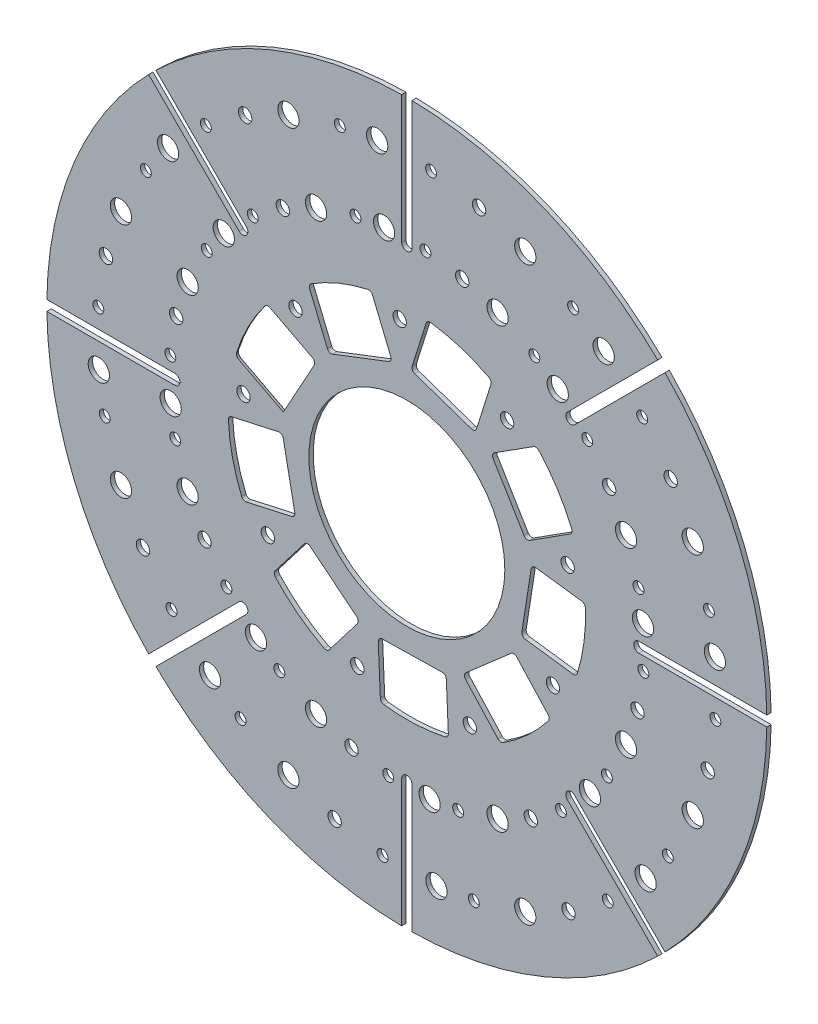
SolidWorks part; units mm, degrees
ref_plane "Plano frontal" through (0, 0, 0) normal (0, 0, 1) x (1, 0, 0)
ref_plane "Plano superior" through (0, 0, 0) normal (0, 1, 0) x (1, 0, 0)
ref_plane "Plano direito" through (0, 0, 0) normal (1, 0, 0) x (0, 0, -1)
sketch "Esboço1" plane through (0, 0, 0) normal (0, 0, 1) x (1, 0, 0)
  circle A0 centre (0, 0) radius 174.5
  circle A1 centre (0, 0) radius 47.5
  dimension "D1" = 349
  dimension "D2" = 95
extrude "Ressalto-extrusão1" add sketch "Esboço1" along normal blind 2.1
sketch "Esboço2" plane through (0, 0, 2.1) normal (0, 0, 1) x (1, 0, 0)
  line L0 (0, 174.5) -> (0, 64.5) construction
  line L1 (-2.5, 239.1223) -> (2.5, 239.1223)
  line L2 (0, 64.5) -> (0, 95.0835) construction
  line L3 (-2.5, 239.1223) -> (-2.5, 112.5)
  line L4 (2.5, 239.1223) -> (2.5, 112.5)
  line L5 (167.3172, 170.8527) -> (170.8527, 167.3172)
  line L6 (167.3172, 170.8527) -> (77.7817, 81.3173)
  line L7 (170.8527, 167.3172) -> (81.3173, 77.7817)
  line L8 (239.1223, 2.5) -> (239.1223, -2.5)
  line L9 (239.1223, 2.5) -> (112.5, 2.5)
  line L10 (239.1223, -2.5) -> (112.5, -2.5)
  line L11 (170.8527, -167.3172) -> (167.3172, -170.8527)
  line L12 (170.8527, -167.3172) -> (81.3173, -77.7817)
  line L13 (167.3172, -170.8527) -> (77.7817, -81.3173)
  line L14 (2.5, -239.1223) -> (-2.5, -239.1223)
  line L15 (2.5, -239.1223) -> (2.5, -112.5)
  line L16 (-2.5, -239.1223) -> (-2.5, -112.5)
  line L17 (-167.3172, -170.8527) -> (-170.8527, -167.3172)
  line L18 (-167.3172, -170.8527) -> (-77.7817, -81.3173)
  line L19 (-170.8527, -167.3172) -> (-81.3173, -77.7817)
  line L20 (-239.1223, -2.5) -> (-239.1223, 2.5)
  line L21 (-239.1223, -2.5) -> (-112.5, -2.5)
  line L22 (-239.1223, 2.5) -> (-112.5, 2.5)
  line L23 (-170.8527, 167.3172) -> (-167.3172, 170.8527)
  line L24 (-170.8527, 167.3172) -> (-81.3173, 77.7817)
  line L25 (-167.3172, 170.8527) -> (-77.7817, 81.3173)
  circle A0 centre (0, 0) radius 174.5 construction
  arc A1 (-2.5, 112.5) -> (2.5, 112.5) centre (0, 112.5) ccw
  arc A2 (77.7817, 81.3173) -> (81.3173, 77.7817) centre (79.5495, 79.5495) ccw
  arc A3 (112.5, 2.5) -> (112.5, -2.5) centre (112.5, 0) ccw
  arc A4 (81.3173, -77.7817) -> (77.7817, -81.3173) centre (79.5495, -79.5495) ccw
  arc A5 (2.5, -112.5) -> (-2.5, -112.5) centre (0, -112.5) ccw
  arc A6 (-77.7817, -81.3173) -> (-81.3173, -77.7817) centre (-79.5495, -79.5495) ccw
  arc A7 (-112.5, -2.5) -> (-112.5, 2.5) centre (-112.5, 0) ccw
  arc A8 (-81.3173, 77.7817) -> (-77.7817, 81.3173) centre (-79.5495, 79.5495) ccw
  point P49 (0, 0)
  dimension "D1" = 2.5
  dimension "D3" = 62
sketch "Esboço3" plane through (0, 0, 2.1) normal (0, 0, 1) x (1, 0, 0)
  line L0 (0, 0) -> (-225.1004, 0) construction
  line L1 (0, 0) -> (-138.5819, 57.4025) construction
  line L2 (0, 0) -> (-126.5087, 80.5949) construction
  line L3 (0, 0) -> (-115.7437, 95.4117) construction
  line L4 (0, 0) -> (-145.8555, 35.0168) construction
  line L5 (0, 0) -> (-149.5376, 11.7689) construction
  circle A0 centre (0, 0) radius 115 construction
  circle A1 centre (0, 0) radius 150 construction
  circle A2 centre (-138.5819, 57.4025) radius 5.15
  circle A3 centre (-106.2461, 44.0086) radius 5.15
  circle A4 centre (-126.5087, 80.5949) radius 2.65
  circle A5 centre (-96.99, 61.7895) radius 2.65
  circle A6 centre (-115.7437, 95.4117) radius 5.15
  circle A7 centre (-88.7368, 73.149) radius 5.15
  circle A8 centre (-145.8555, 35.0168) radius 3.25
  circle A9 centre (-111.8225, 26.8462) radius 3.25
  circle A10 centre (-114.6455, 9.0228) radius 2.65
  circle A11 centre (-149.5376, 11.7689) radius 2.65
  circle A12 centre (-57.4025, 138.5819) radius 5.15
  circle A13 centre (-44.0086, 106.2461) radius 5.15
  circle A14 centre (-32.4659, 146.4444) radius 2.65
  circle A15 centre (-24.8906, 112.274) radius 2.65
  circle A16 centre (-14.3769, 149.3094) radius 5.15
  circle A17 centre (-11.0223, 114.4706) radius 5.15
  circle A18 centre (-78.3748, 127.896) radius 3.25
  circle A19 centre (-60.0873, 98.0536) radius 3.25
  circle A20 centre (-74.6865, 87.4467) radius 2.65
  circle A21 centre (-97.4172, 114.0609) radius 2.65
  circle A22 centre (57.4025, 138.5819) radius 5.15
  circle A23 centre (44.0086, 106.2461) radius 5.15
  circle A24 centre (80.5949, 126.5087) radius 2.65
  circle A25 centre (61.7895, 96.99) radius 2.65
  circle A26 centre (95.4117, 115.7437) radius 5.15
  circle A27 centre (73.149, 88.7368) radius 5.15
  circle A28 centre (35.0168, 145.8555) radius 3.25
  circle A29 centre (26.8462, 111.8225) radius 3.25
  circle A30 centre (9.0228, 114.6455) radius 2.65
  circle A31 centre (11.7689, 149.5376) radius 2.65
  circle A32 centre (138.5819, 57.4025) radius 5.15
  circle A33 centre (106.2461, 44.0086) radius 5.15
  circle A34 centre (146.4444, 32.4659) radius 2.65
  circle A35 centre (112.274, 24.8906) radius 2.65
  circle A36 centre (149.3094, 14.3769) radius 5.15
  circle A37 centre (114.4706, 11.0223) radius 5.15
  circle A38 centre (127.896, 78.3748) radius 3.25
  circle A39 centre (98.0536, 60.0873) radius 3.25
  circle A40 centre (87.4467, 74.6865) radius 2.65
  circle A41 centre (114.0609, 97.4172) radius 2.65
  circle A42 centre (138.5819, -57.4025) radius 5.15
  circle A43 centre (106.2461, -44.0086) radius 5.15
  circle A44 centre (126.5087, -80.5949) radius 2.65
  circle A45 centre (96.99, -61.7895) radius 2.65
  circle A46 centre (115.7437, -95.4117) radius 5.15
  circle A47 centre (88.7368, -73.149) radius 5.15
  circle A48 centre (145.8555, -35.0168) radius 3.25
  circle A49 centre (111.8225, -26.8462) radius 3.25
  circle A50 centre (114.6455, -9.0228) radius 2.65
  circle A51 centre (149.5376, -11.7689) radius 2.65
  circle A52 centre (57.4025, -138.5819) radius 5.15
  circle A53 centre (44.0086, -106.2461) radius 5.15
  circle A54 centre (32.4659, -146.4444) radius 2.65
  circle A55 centre (24.8906, -112.274) radius 2.65
  circle A56 centre (14.3769, -149.3094) radius 5.15
  circle A57 centre (11.0223, -114.4706) radius 5.15
  circle A58 centre (78.3748, -127.896) radius 3.25
  circle A59 centre (60.0873, -98.0536) radius 3.25
  circle A60 centre (74.6865, -87.4467) radius 2.65
  circle A61 centre (97.4172, -114.0609) radius 2.65
  circle A62 centre (-57.4025, -138.5819) radius 5.15
  circle A63 centre (-44.0086, -106.2461) radius 5.15
  circle A64 centre (-80.5949, -126.5087) radius 2.65
  circle A65 centre (-61.7895, -96.99) radius 2.65
  circle A66 centre (-95.4117, -115.7437) radius 5.15
  circle A67 centre (-73.149, -88.7368) radius 5.15
  circle A68 centre (-35.0168, -145.8555) radius 3.25
  circle A69 centre (-26.8462, -111.8225) radius 3.25
  circle A70 centre (-9.0228, -114.6455) radius 2.65
  circle A71 centre (-11.7689, -149.5376) radius 2.65
  circle A72 centre (-138.5819, -57.4025) radius 5.15
  circle A73 centre (-106.2461, -44.0086) radius 5.15
  circle A74 centre (-146.4444, -32.4659) radius 2.65
  circle A75 centre (-112.274, -24.8906) radius 2.65
  circle A76 centre (-149.3094, -14.3769) radius 5.15
  circle A77 centre (-114.4706, -11.0223) radius 5.15
  circle A78 centre (-127.896, -78.3748) radius 3.25
  circle A79 centre (-98.0536, -60.0873) radius 3.25
  circle A80 centre (-87.4467, -74.6865) radius 2.65
  circle A81 centre (-114.0609, -97.4172) radius 2.65
  point P172 (0, 0)
  dimension "D1" = 300
  dimension "D3" = 10.3
  dimension "D4" = 10
  dimension "D5" = 5.3
  dimension "D9" = 8
  dimension "D10" = 6.5
  dimension "D11" = 6.5
  dimension "D2" = 22.5
  dimension "D6" = 17
  dimension "D7" = 9
  dimension "D8" = 9
extrude "Corte-extrusão2" cut sketch "Esboço3" against normal through all
sketch "Esboço4" plane through (0, 0, 2.1) normal (0, 0, 1) x (1, 0, 0)
sketch "Esboço5" plane through (0, 0, 2.1) normal (0, 0, 1) x (1, 0, 0)
extrude "Corte-extrusão3" cut sketch "Esboço2" against normal through all
sketch "Esboço6" plane through (0, 0, 2.1) normal (0, 0, 1) x (1, 0, 0)
  line L0 (0, 0) -> (0, 79.85) construction
  line L1 (0, 0) -> (-30.5573, 73.7718) construction
  line L2 (0, 0) -> (-3.483, 79.774) construction
  circle A0 centre (0, 0) radius 79.85 construction
  circle A1 centre (-3.483, 79.774) radius 3.25
  circle A2 centre (48.6096, 63.3493) radius 3.25
  circle A3 centre (77.9572, 17.2827) radius 3.25
  circle A4 centre (70.8278, -36.8706) radius 3.25
  circle A5 centre (30.5573, -73.7718) radius 3.25
  circle A6 centre (-24.0114, -76.1543) radius 3.25
  circle A7 centre (-67.3448, -42.9034) radius 3.25
  circle A8 centre (-79.1669, 10.4225) radius 3.25
  circle A9 centre (-53.9459, 58.8716) radius 3.25
  point P25 (0, 0)
  dimension "D1" = 159.7
  dimension "D4" = 6.5
  dimension "D2" = 22.5
  dimension "D3" = 20
extrude "Corte-extrusão4" cut sketch "Esboço6" against normal through all
sketch "Esboço7" plane through (0, 0, 2.1) normal (0, 0, 1) x (1, 0, 0)
  line L0 (-37.7817, 48.1096) -> (-6.9923, 59.9843)
  line L1 (1.9818, 61.1397) -> (33.2008, 50.4452)
  line L2 (-3.483, 79.774) -> (0, 0) construction
  line L3 (-6.9923, 59.9843) -> (-17.2943, 84.8556)
  line L4 (33.2008, 50.4452) -> (41.2959, 76.1197)
  line L5 (-37.7817, 48.1096) -> (-47.7731, 72.2308)
  line L6 (1.9818, 61.1397) -> (9.8328, 86.04)
  line L7 (40.8179, 45.5618) -> (57.8589, 17.3022)
  line L8 (57.8589, 17.3022) -> (80.5633, 31.7665)
  line L9 (40.8179, 45.5618) -> (62.8378, 59.59)
  line L10 (60.555, 8.6651) -> (55.4441, -23.9367)
  line L11 (55.4441, -23.9367) -> (82.1342, -27.4505)
  line L12 (60.555, 8.6651) -> (86.4403, 5.2573)
  line L13 (51.9576, -32.2861) -> (27.0864, -53.9754)
  line L14 (27.0864, -53.9754) -> (45.2736, -73.8232)
  line L15 (51.9576, -32.2861) -> (69.5964, -51.5354)
  line L16 (19.0487, -58.1303) -> (-13.9453, -58.7583)
  line L17 (-13.9453, -58.7583) -> (-12.771, -85.6531)
  line L18 (19.0487, -58.1303) -> (20.1876, -84.2141)
  line L19 (-22.7733, -56.7747) -> (-48.4518, -36.0476)
  line L20 (-48.4518, -36.0476) -> (-64.84, -57.4051)
  line L21 (-22.7733, -56.7747) -> (-38.6672, -77.4881)
  line L22 (-53.9394, -28.8536) -> (-60.2872, 3.5301)
  line L23 (-60.2872, 3.5301) -> (-86.5695, -2.2965)
  line L24 (-53.9394, -28.8536) -> (-79.4292, -34.5045)
  line L25 (-59.8667, 12.5685) -> (-43.9136, 41.4561)
  line L26 (-43.9136, 41.4561) -> (-67.7923, 53.8866)
  line L27 (-59.8667, 12.5685) -> (-83.0254, 24.6241)
  arc A0 (9.8328, 86.04) -> (41.2959, 76.1197) centre (0, 0) cw
  arc A1 (-47.7731, 72.2308) -> (-17.2943, 84.8556) centre (0, 0) cw
  arc A2 (62.8378, 59.59) -> (80.5633, 31.7665) centre (0, 0) cw
  arc A3 (86.4403, 5.2573) -> (82.1342, -27.4505) centre (0, 0) cw
  arc A4 (69.5964, -51.5354) -> (45.2736, -73.8232) centre (0, 0) cw
  arc A5 (20.1876, -84.2141) -> (-12.771, -85.6531) centre (0, 0) cw
  arc A6 (-38.6672, -77.4881) -> (-64.84, -57.4051) centre (0, 0) cw
  arc A7 (-79.4292, -34.5045) -> (-86.5695, -2.2965) centre (0, 0) cw
  arc A8 (-83.0254, 24.6241) -> (-67.7923, 53.8866) centre (0, 0) cw
  point P43 (0, 0)
extrude "Corte-extrusão5" cut sketch "Esboço7" against normal through all
fillet "Filete1" radius 2 39 edges at (-71.446, 18.5963, 0) (-76.8151, 39.9874, 0) (-55.8529, 47.6714, 0) (-22.7733, -56.7747, 1.05) (-38.6672, -77.4881, 1.05) (-64.84, -57.4051, 1.05) (-48.4518, -36.0476, 1.05) (20.1876, -84.2141, 1.05) (-12.771, -85.6531, 1.05) (-13.9453, -58.7583, 1.05) (19.0487, -58.1303, 1.05) (51.9576, -32.2861, 1.05) (27.0864, -53.9754, 1.05) (45.2736, -73.8232, 1.05) (69.5964, -51.5354, 1.05) (82.1342, -27.4505, 1.05) (55.4441, -23.9367, 1.05) (60.555, 8.6651, 1.05) (86.4403, 5.2573, 1.05) (62.8378, 59.59, 1.05) (40.8179, 45.5618, 1.05) (57.8589, 17.3022, 1.05) (80.5633, 31.7665, 1.05) (33.2008, 50.4452, 1.05) (1.9818, 61.1397, 1.05) (9.8328, 86.04, 1.05) (41.2959, 76.1197, 1.05) (-6.9923, 59.9843, 1.05) (-37.7817, 48.1096, 1.05) (-47.7731, 72.2308, 1.05) (-17.2943, 84.8556, 1.05) (-43.9136, 41.4561, 1.05) (-67.7923, 53.8866, 1.05) (-83.0254, 24.6241, 1.05) (-51.8901, 27.0123, 0) (-53.9394, -28.8536, 1.05) (-79.4292, -34.5045, 1.05) (-86.5695, -2.2965, 1.05) (-60.2872, 3.5301, 1.05)
